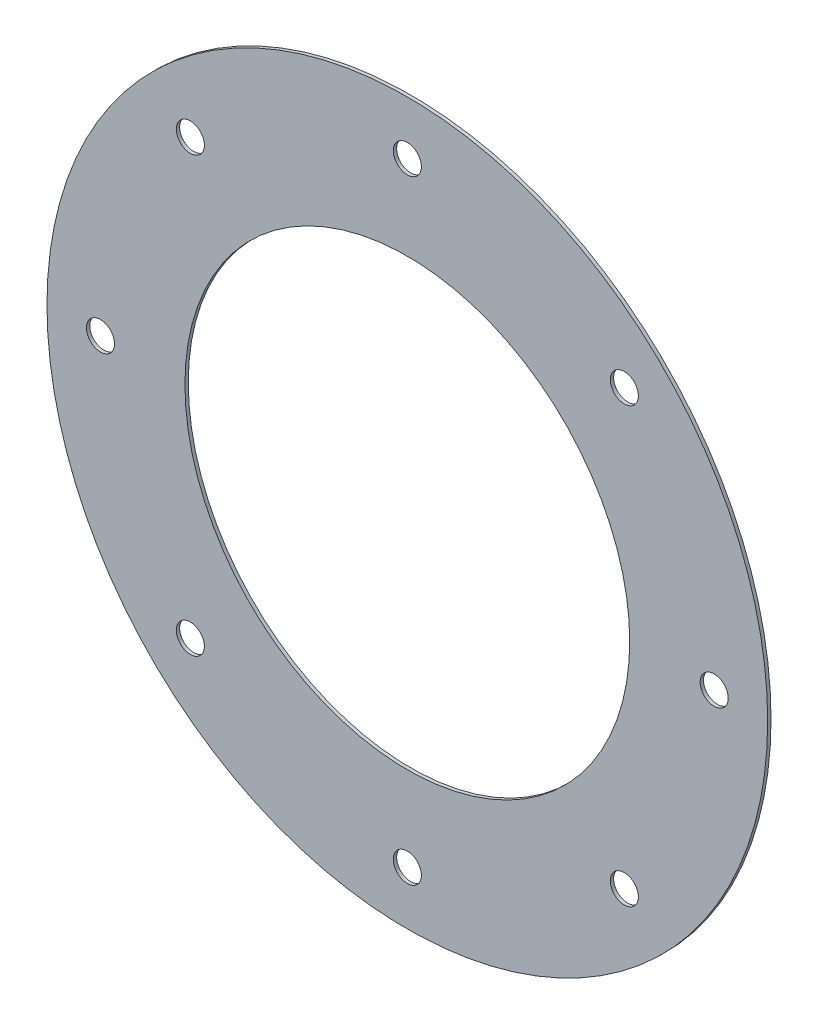
SolidWorks part; units mm, degrees
ref_plane "Front Plane" through (0, 0, 0) normal (0, 0, 1) x (1, 0, 0)
ref_plane "Top Plane" through (0, 0, 0) normal (0, 1, 0) x (1, 0, 0)
ref_plane "Right Plane" through (0, 0, 0) normal (1, 0, 0) x (0, 0, -1)
sketch "Sketch1" plane through (0, 0, 0) normal (0, 0, 1) x (1, 0, 0)
  circle A0 centre (0, 0) radius 53.875
  circle A1 centre (0, 0) radius 33.25
  circle A2 centre (0, 0) radius 45.875 construction
  circle A3 centre (0, 45.875) radius 2.1
  circle A4 centre (32.4385, 32.4385) radius 2.1
  circle A5 centre (45.875, 0) radius 2.1
  circle A6 centre (32.4385, -32.4385) radius 2.1
  circle A7 centre (0, -45.875) radius 2.1
  circle A8 centre (-32.4385, -32.4385) radius 2.1
  circle A9 centre (-45.875, 0) radius 2.1
  circle A10 centre (-32.4385, 32.4385) radius 2.1
  point P7 (0, 53.875)
  point P9 (-31.3982, 27.1437)
  point P10 (0, 0)
  point P22 (0, 0)
  point P25 (0, 0)
  dimension "D1" = 107.75
  dimension "D2" = 66.5
  dimension "D3" = 8
  dimension "D4" = 4.2
  dimension "D5" = 8
extrude "Boss-Extrude1" add sketch "Sketch1" along normal blind 0.5
